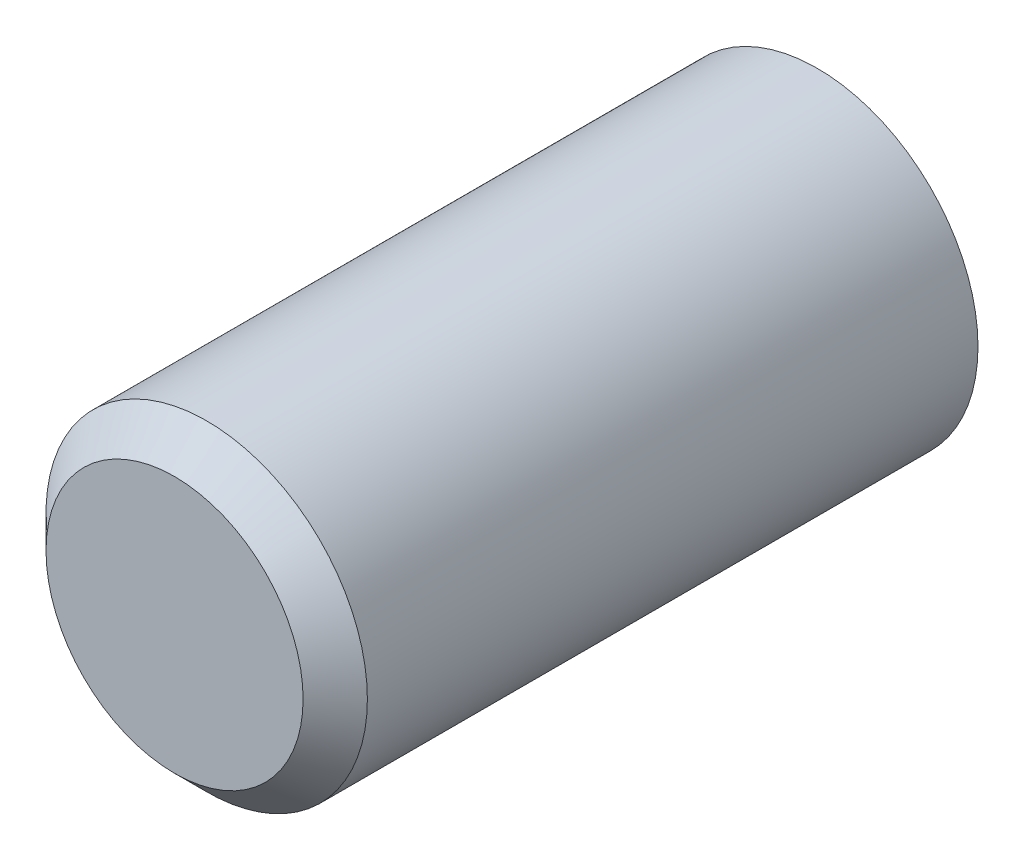
SolidWorks part; units mm, degrees
ref_plane "Спереди" through (0, 0, 0) normal (0, 0, 1) x (1, 0, 0)
ref_plane "Сверху" through (0, 0, 0) normal (0, 1, 0) x (1, 0, 0)
ref_plane "Справа" through (0, 0, 0) normal (1, 0, 0) x (0, 0, -1)
sketch "Эскиз1" plane through (0, 0, 0) normal (0, 0, 1) x (1, 0, 0)
  circle A0 centre (0, 0) radius 25
  dimension "D1" = 50
extrude "Бобышка-Вытянуть1" add sketch "Эскиз1" along normal blind 100
chamfer "Фаска1" distance 5 angle 45 1 edges at (25, 0, 100)
